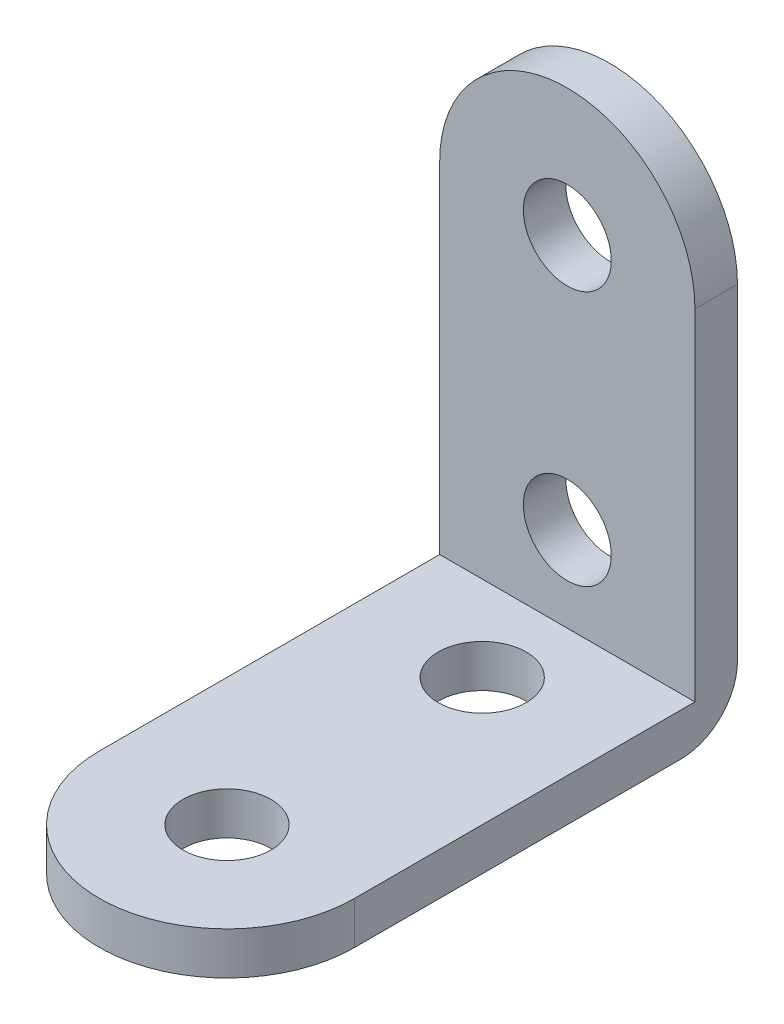
SolidWorks part; units mm, degrees
ref_plane "Alzado" through (0, 0, 0) normal (0, 0, 1) x (1, 0, 0)
ref_plane "Planta" through (0, 0, 0) normal (0, 1, 0) x (1, 0, 0)
ref_plane "Vista lateral" through (0, 0, 0) normal (1, 0, 0) x (0, 0, -1)
sketch "Croquis1" plane through (0, 0, 0) normal (0, 1, 0) x (1, 0, 0)
  line L0 (-4.5, 0) -> (-4.5, 13.5)
  line L1 (4.5, 0) -> (4.5, 13.5)
  line L2 (-4.5, 13.5) -> (4.5, 13.5)
  line L3 (4.5, 13.5) -> (4.3582, 13.5989)
  circle A0 centre (0, 0) radius 4.5
  circle A1 centre (0, 0) radius 1.55
extrude "Saliente-Extruir1" add sketch "Croquis1" along normal blind 1.5 contours A0 L1 L2 L0 | A0 A1
sketch "Croquis2" plane through (0, 1.5, 0) normal (0, 1, 0) x (1, 0, 0)
  line L0 (-4.5, 12) -> (4.5, 12)
  line L1 (-4.5, 0) -> (-4.5, 13.5) construction
  line L2 (4.5, 0) -> (4.5, 13.5) construction
sketch "Croquis6" plane through (0, 1.5, 0) normal (0, 1, 0) x (1, 0, 0)
  circle A0 centre (0, 9) radius 1.55
extrude "Cortar-Extruir1" cut sketch "Croquis6" against normal blind 1.5
ref_plane "Plano3" through (0, 6.75, -6.75) normal (0, 0.7071, -0.7071) x (-1, 0, 0)
mirror "Simetría1" about plane through (0, 6.75, -6.75) normal (0, 0.7071, -0.7071) of "Saliente-Extruir1", "Cortar-Extruir1"
fillet "Redondeo1" radius 2 1 edges at (0, 0, -13.5)
